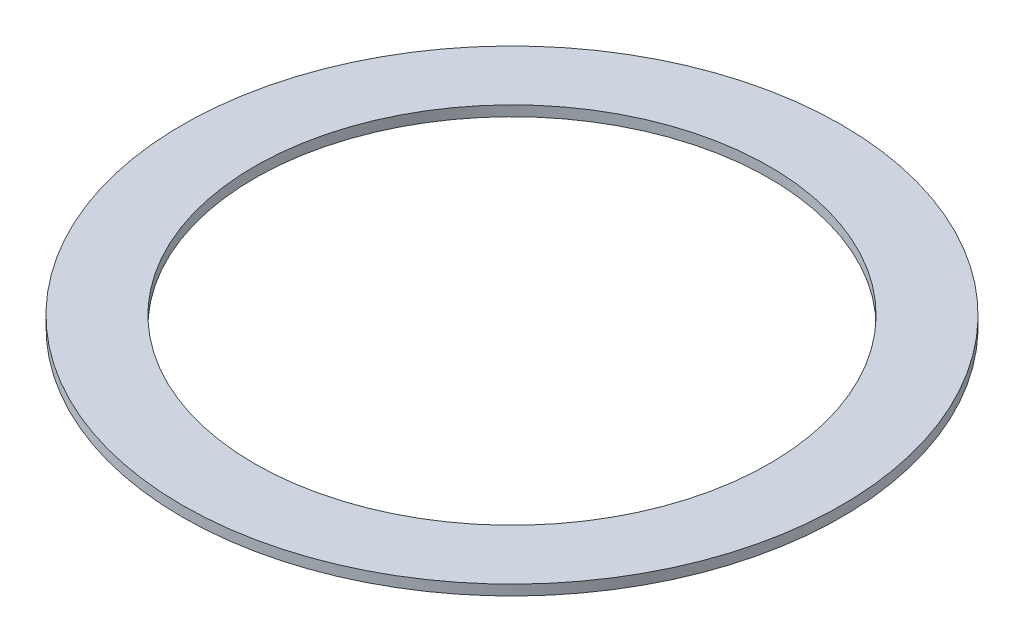
SolidWorks part; units mm, degrees
ref_plane "Front" through (0, 0, 0) normal (0, 0, 1) x (1, 0, 0)
ref_plane "Top" through (0, 0, 0) normal (0, 1, 0) x (1, 0, 0)
ref_plane "Right" through (0, 0, 0) normal (1, 0, 0) x (0, 0, -1)
other "Configuration Table"
sketch "Esquisse1" plane through (0, 0, 0) normal (0, 1, 0) x (1, 0, 0)
  circle A0 centre (0, 0) radius 12.5
  circle A1 centre (0, 0) radius 16
  dimension "D1" = 25
  dimension "D2" = 32
extrude "Boss.-Extru.1" add sketch "Esquisse1" along normal blind 0.5
